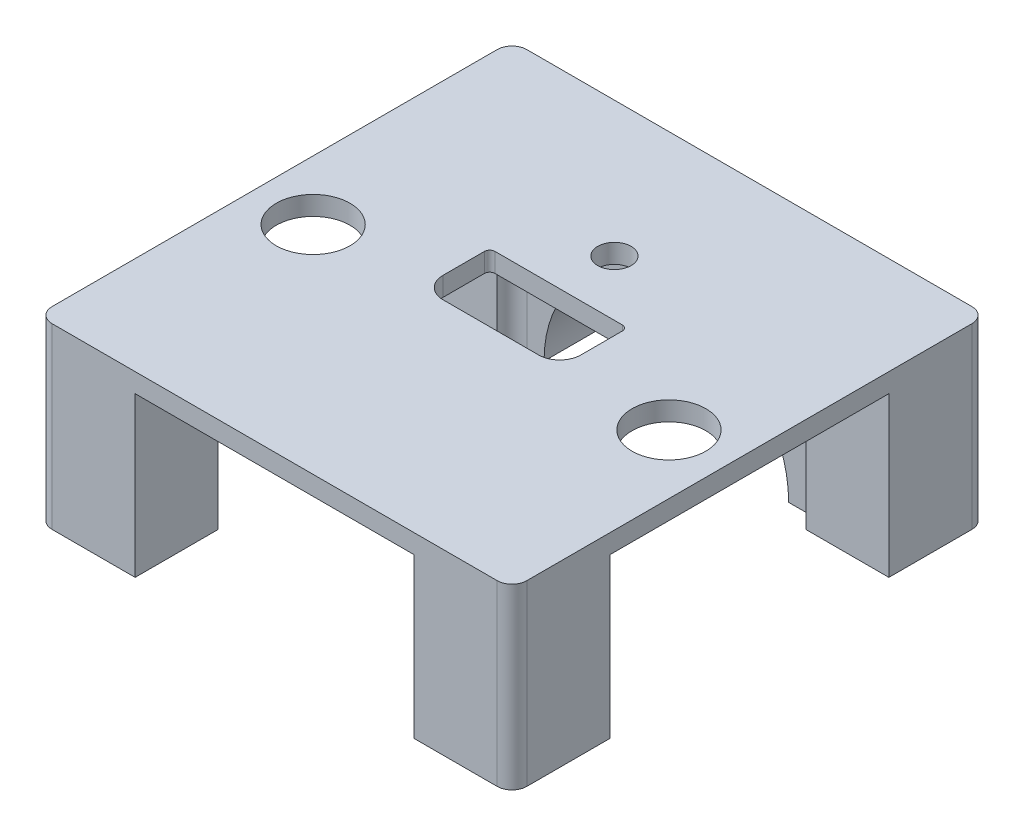
SolidWorks part; units mm, degrees
ref_plane "Front Plane" through (0, 0, 0) normal (0, 0, 1) x (1, 0, 0)
ref_plane "Top Plane" through (0, 0, 0) normal (0, 1, 0) x (1, 0, 0)
ref_plane "Right Plane" through (0, 0, 0) normal (1, 0, 0) x (0, 0, -1)
sketch "Sketch1" plane through (0, 0, 0) normal (0, 1, 0) x (1, 0, 0)
  line L0 (0, 8.08) -> (0, 11.23) construction
  line L1 (-11.25, -12.65) -> (11.25, -12.65)
  line L2 (-12.65, -11.25) -> (-12.65, 11.25)
  line L3 (-11.25, 12.65) -> (11.25, 12.65)
  line L4 (12.65, -11.25) -> (12.65, 11.25)
  line L5 (-12.65, -12.65) -> (12.65, 12.65) construction
  line L6 (-12.65, 12.65) -> (12.65, -12.65) construction
  arc A0 (-12.65, -11.25) -> (-11.25, -12.65) centre (-11.25, -11.25) ccw
  arc A1 (12.65, -11.25) -> (11.25, -12.65) centre (11.25, -11.25) cw
  arc A2 (12.65, 11.25) -> (11.25, 12.65) centre (11.25, 11.25) ccw
  arc A3 (-11.25, 12.65) -> (-12.65, 11.25) centre (-11.25, 11.25) ccw
  circle A4 centre (0, 9.655) radius 1.575
  point P0 (0, 0)
  point P20 (0, 12.65)
  point P25 (0, 9.655)
  dimension "D2" = 1.4
  dimension "D3" = 1.42
  dimension "D4" = 3.15
  dimension "D1" = 25.3
sketch "Sketch2" plane through (0, 0, 0) normal (0, 1, 0) x (1, 0, 0)
  line L1 (-20.975, -22.375) -> (20.975, -22.375)
  line L7 (-22.375, -20.975) -> (-22.375, 20.975)
  line L8 (-4.5, -2) -> (4.5, -2)
  line L9 (-6.5, 0) -> (-6.5, 3.9)
  line L10 (-6, 4.4) -> (6, 4.4)
  line L11 (6.5, 0) -> (6.5, 3.9)
  line L12 (-20.975, 22.375) -> (20.975, 22.375)
  line L13 (22.375, -20.975) -> (22.375, 20.975)
  line L14 (-22.375, -22.375) -> (22.375, 22.375) construction
  line L15 (-22.375, 22.375) -> (22.375, -22.375) construction
  arc A3 (-6.5, 0) -> (-4.5, -2) centre (-4.5, 0) ccw
  arc A4 (6.5, 0) -> (4.5, -2) centre (4.5, 0) cw
  arc A5 (6.5, 3.9) -> (6, 4.4) centre (6, 3.9) ccw
  arc A6 (-6.5, 3.9) -> (-6, 4.4) centre (-6, 3.9) cw
  arc A7 (-22.375, -20.975) -> (-20.975, -22.375) centre (-20.975, -20.975) ccw
  arc A8 (20.975, -22.375) -> (22.375, -20.975) centre (20.975, -20.975) ccw
  arc A9 (22.375, 20.975) -> (20.975, 22.375) centre (20.975, 20.975) ccw
  arc A10 (-22.375, 20.975) -> (-20.975, 22.375) centre (-20.975, 20.975) cw
  circle A11 centre (0, 9.655) radius 1.575
  point P0 (0, 0)
  point P8 (0, 0)
  point P11 (0, 0)
  point P12 (0, 4.4)
  dimension "D1" = 2
  dimension "D2" = 0.5
  dimension "D6" = 1.4
  dimension "D3" = 13
  dimension "D4" = 4.4
  dimension "D5" = 44.75
extrude "Boss-Extrude3" add sketch "Sketch2" along normal blind 1.8
sketch "Sketch3" plane through (0, 0, 0) normal (0, -1, 0) x (1, 0, 0)
  line L1 (-20.975, -22.375) -> (20.975, -22.375)
  line L2 (-22.375, -20.975) -> (-22.375, -13.15)
  line L3 (-20.975, 22.375) -> (-13.15, 22.375)
  line L4 (22.375, -20.975) -> (22.375, -13.15)
  line L5 (-22.375, -22.375) -> (22.375, 22.375) construction
  line L6 (-22.375, 22.375) -> (22.375, -22.375) construction
  line L7 (-14.55, 13.15) -> (-22.375, 13.15)
  line L8 (-13.15, -14.55) -> (13.15, -14.55)
  line L12 (-14.55, -14.55) -> (14.55, 14.55) construction
  line L13 (-14.55, 14.55) -> (14.55, -14.55) construction
  line L14 (-14.55, -13.15) -> (-22.375, -13.15)
  line L15 (14.55, 13.15) -> (22.375, 13.15)
  line L16 (14.55, -13.15) -> (22.375, -13.15)
  line L17 (-22.375, 13.15) -> (-22.375, 20.975)
  line L18 (22.375, 13.15) -> (22.375, 20.975)
  line L19 (-13.15, 14.55) -> (-13.15, 22.375)
  line L20 (13.15, 14.55) -> (13.15, 22.375)
  line L21 (13.15, 22.375) -> (20.975, 22.375)
  arc A0 (20.975, -22.375) -> (22.375, -20.975) centre (20.975, -20.975) ccw
  arc A1 (22.375, 20.975) -> (20.975, 22.375) centre (20.975, 20.975) ccw
  arc A2 (-20.975, -22.375) -> (-22.375, -20.975) centre (-20.975, -20.975) cw
  arc A3 (-22.375, 20.975) -> (-20.975, 22.375) centre (-20.975, 20.975) cw
  arc A4 (13.15, -14.55) -> (14.55, -13.15) centre (13.15, -13.15) ccw
  arc A5 (14.55, 13.15) -> (13.15, 14.55) centre (13.15, 13.15) ccw
  arc A6 (-13.15, 14.55) -> (-14.55, 13.15) centre (-13.15, 13.15) ccw
  arc A7 (-13.15, -14.55) -> (-14.55, -13.15) centre (-13.15, -13.15) cw
  point P0 (0, 0)
  point P18 (0, 0)
  dimension "D2" = 1.4
  dimension "D3" = 1.4
  dimension "D1" = 44.75
  dimension "D4" = 26.3
extrude "Boss-Extrude4" add sketch "Sketch3" along normal blind 15
sketch "Sketch4" plane through (0, 0, -22.375) normal (0, 0, -1) x (-1, 0, 0)
  line L0 (20.975, -15) -> (-20.975, -15) construction
  circle A0 centre (0, -15) radius 11.5302
extrude "Cut-Extrude1" cut sketch "Sketch4" against normal up to next
sketch "Sketch5" plane through (0, 1.8, 0) normal (0, 1, 0) x (1, 0, 0)
  circle A0 centre (-16.77, -1.975) radius 3.475
  circle A1 centre (16.77, -1.975) radius 3.475
  dimension "D1" = 6.95
  dimension "D2" = 6.95
extrude "Cut-Extrude2" cut sketch "Sketch5" against normal through all
equation "\"D1@Sketch3\"=\"D5@Sketch2\""
